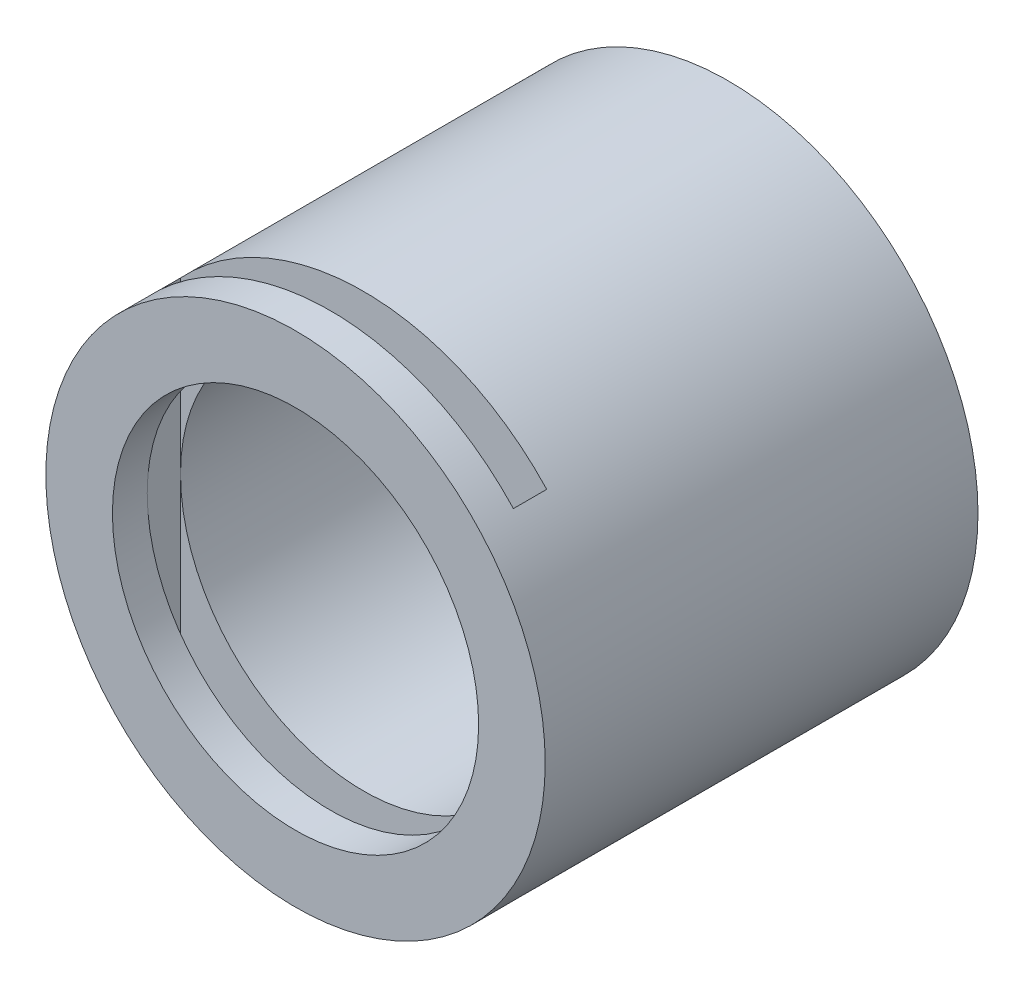
SolidWorks part; units mm, degrees
material "ABS"
ref_plane "Front Plane" through (0, 0, 0) normal (0, 0, 1) x (1, 0, 0)
ref_plane "Top Plane" through (0, 0, 0) normal (0, 1, 0) x (1, 0, 0)
ref_plane "Right Plane" through (0, 0, 0) normal (1, 0, 0) x (0, 0, -1)
sketch "Sketch1" plane through (0, 0, 0) normal (0, 0, 1) x (1, 0, 0)
  circle A0 centre (0, 0) radius 15
  dimension "D1" = 30
extrude "Boss-Extrude5" add sketch "Sketch1" along normal blind 26 contours A0
sketch "Sketch3" plane through (0, 0, 26) normal (0, 0, 1) x (1, 0, 0)
  circle A0 centre (0, 0) radius 5.625
  dimension "D1" = 11.25
extrude "Cut-Extrude2" cut sketch "Sketch3" against normal through all
sketch "Sketch4" plane through (0, 0, 26) normal (0, 0, 1) x (1, 0, 0)
  circle A0 centre (0, 0) radius 11
  circle A2 centre (0, 0) radius 15 construction
  dimension "D1" = 22
  dimension "D2" = 4
extrude "Cut-Extrude3" cut sketch "Sketch4" against normal blind 20
sketch "Sketch6" plane through (0, 0, 0) normal (0, 1, 0) x (1, 0, 0)
  line L0 (-11, -6) -> (-11, -26) construction
  line L1 (11, -26) -> (11, -6) construction
  line L2 (-11, -21.9096) -> (11, -21.9096)
  line L3 (-11, -21.9096) -> (-11, -23.9096)
  line L4 (-11, -23.9096) -> (11, -23.9096)
  line L9 (11, -21.9096) -> (11, -23.9096)
  dimension "D2" = 2
extrude "Cut-Extrude4" cut sketch "Sketch6" against normal through all and the other way through all
sketch "Sketch7" plane through (0, 0, 0) normal (0, 0, 1) x (1, 0, 0)
  circle A1 centre (0, 0) radius 11
  circle A2 centre (0, 0) radius 9
extrude "Cut-Extrude6" cut sketch "Sketch7" against normal blind 2 from surface at 6 starting at face at (11, 0, 6)
